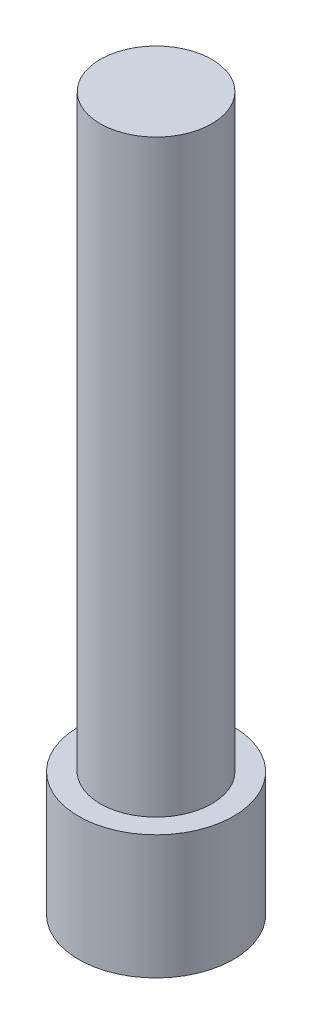
SolidWorks part; units mm, degrees
ref_plane "Front Plane" through (0, 0, 0) normal (0, 0, 1) x (1, 0, 0)
ref_plane "Top Plane" through (0, 0, 0) normal (0, 1, 0) x (1, 0, 0)
ref_plane "Right Plane" through (0, 0, 0) normal (1, 0, 0) x (0, 0, -1)
sketch "Sketch1" plane through (0, 0, 0) normal (0, 1, 0) x (1, 0, 0)
  circle A0 centre (0, 0) radius 0.9
  dimension "D1" = 1.8
extrude "Boss-Extrude1" add sketch "Sketch1" along normal blind 9.5
sketch "Sketch2" plane through (0, 0, 0) normal (0, -1, 0) x (1, 0, 0)
  circle A0 centre (0, 0) radius 1.25
  dimension "D1" = 2.5
extrude "Boss-Extrude2" add sketch "Sketch2" along normal blind 2
